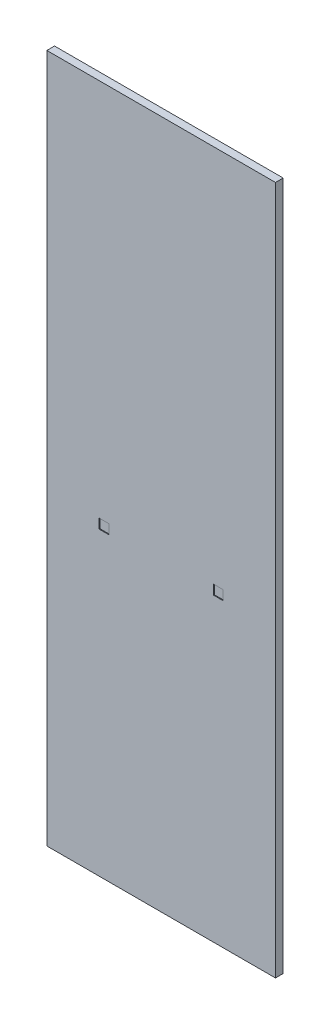
SolidWorks part; units mm, degrees
ref_plane "Front Plane" through (0, 0, 0) normal (0, 0, 1) x (1, 0, 0)
ref_plane "Top Plane" through (0, 0, 0) normal (0, 1, 0) x (1, 0, 0)
ref_plane "Right Plane" through (0, 0, 0) normal (1, 0, 0) x (0, 0, -1)
sketch "Sketch1" plane through (0, 0, 0) normal (0, 0, 1) x (1, 0, 0)
  line L1 (298, -898) -> (-298, -898)
  line L2 (298, -898) -> (298, 898)
  line L3 (298, 898) -> (-298, 898)
  line L4 (-298, -898) -> (-298, 898)
  line L5 (298, -898) -> (-298, 898) construction
  line L6 (298, 898) -> (-298, -898) construction
  point P0 (0, 0)
  dimension "D1" = 596
  dimension "D2" = 1796
extrude "Boss-Extrude1" add sketch "Sketch1" along normal blind 20
sketch "Sketch2" plane through (0, 0, 20) normal (0, 0, 1) x (1, 0, 0)
  line L0 (298, -102) -> (-298, -102) construction
  line L1 (298, -898) -> (298, 898) construction
  line L2 (-298, 898) -> (-298, -898) construction
  line L3 (298, 898) -> (-298, 898) construction
  line L4 (-149, 898) -> (-149, -898) construction
  line L5 (-298, -898) -> (298, -898) construction
  line L6 (149, 898) -> (149, -898) construction
  line L8 (-136.5, -114.5) -> (-161.5, -114.5)
  line L9 (-136.5, -114.5) -> (-136.5, -89.5)
  line L10 (-136.5, -89.5) -> (-161.5, -89.5)
  line L11 (-161.5, -114.5) -> (-161.5, -89.5)
  line L12 (-136.5, -114.5) -> (-161.5, -89.5) construction
  line L13 (-136.5, -89.5) -> (-161.5, -114.5) construction
  line L14 (161.5, -114.5) -> (136.5, -114.5)
  line L15 (161.5, -114.5) -> (161.5, -89.5)
  line L16 (161.5, -89.5) -> (136.5, -89.5)
  line L17 (136.5, -114.5) -> (136.5, -89.5)
  line L18 (161.5, -114.5) -> (136.5, -89.5) construction
  line L19 (161.5, -89.5) -> (136.5, -114.5) construction
  point P15 (-149, -102)
  point P20 (149, -102)
  dimension "D4" = 25
  dimension "D5" = 25
  dimension "D1" = 1000
  dimension "D2" = 149
  dimension "D3" = 149
  dimension "D6" = 25
  dimension "D7" = 25
extrude "Cut-Extrude1" cut sketch "Sketch2" against normal blind 2
sketch "Sketch3" plane through (0, 0, 20) normal (0, 0, 1) x (1, 0, 0)
  line L0 (0, 1012.9749) -> (0, -1086.4881) construction
  line L1 (-161.5, -102) -> (223.2509, -102) construction
  line L2 (-161.5, -89.5) -> (-161.5, -114.5) construction
  line L3 (-136.5, -114.5) -> (-136.5, -89.5) construction
  line L4 (136.5, -89.5) -> (136.5, -114.5) construction
  line L5 (-298, 898) -> (-298, -898) construction
  line L6 (298, -898) -> (298, 898) construction
  line L7 (298, 102) -> (-298, 102) construction
  line L8 (-298, -898) -> (298, -898) construction
  dimension "D1" = 298
  dimension "D2" = 298
  dimension "D3" = 136.5
  dimension "D4" = 136.5
  dimension "D5" = 1000
  dimension "D6" = 204
